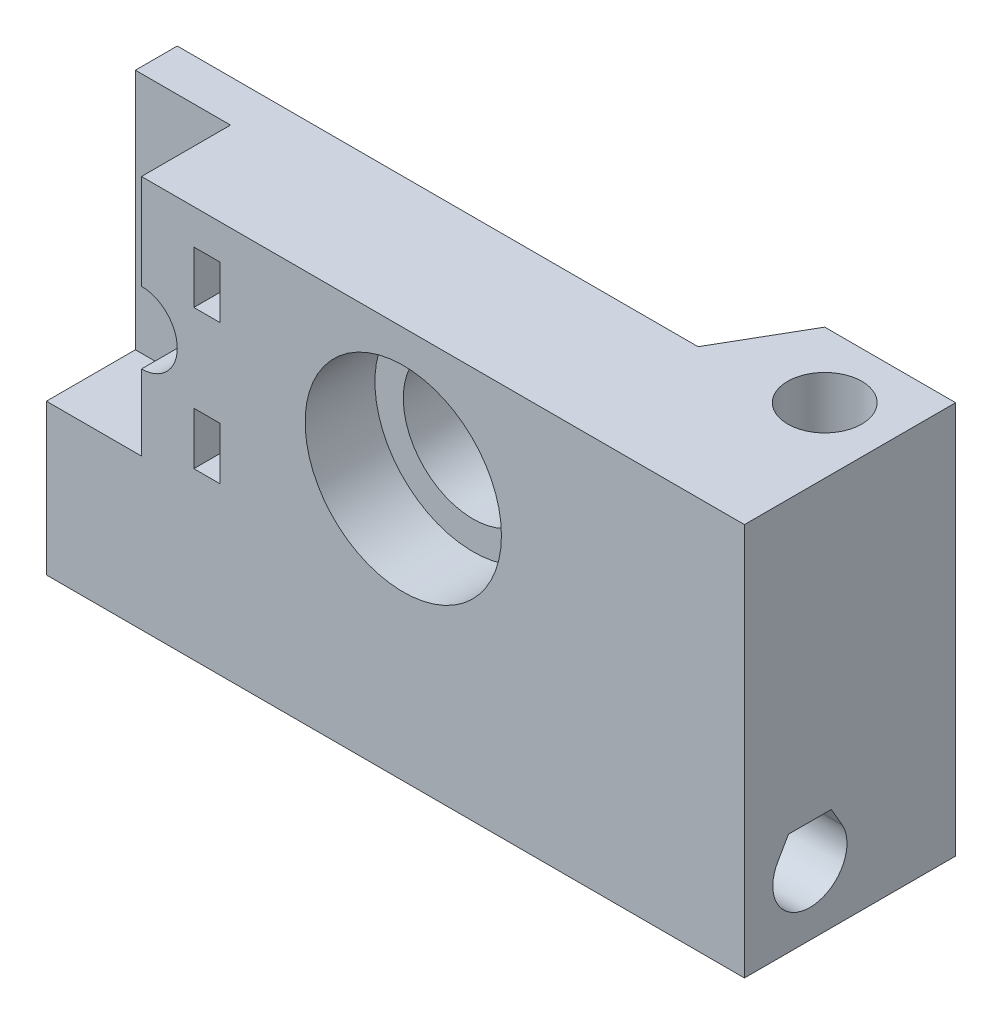
SolidWorks part; units mm, degrees
ref_plane "Piano frontale" through (0, 0, 0) normal (0, 0, 1) x (1, 0, 0)
ref_plane "Piano superiore" through (0, 0, 0) normal (0, 1, 0) x (1, 0, 0)
ref_plane "Piano destro" through (0, 0, 0) normal (1, 0, 0) x (0, 0, -1)
sketch "Schizzo2" plane through (0, 0, 0) normal (0, 0, 1) x (1, 0, 0)
  line L1 (40, -15) -> (-40, -15)
  line L2 (40, -15) -> (40, 15)
  line L3 (40, 15) -> (-40, 15)
  line L4 (-40, -15) -> (-40, 15)
  line L5 (40, -15) -> (-40, 15) construction
  line L6 (40, 15) -> (-40, -15) construction
  point P0 (0, 0)
  dimension "D1" = 30
  dimension "D2" = 80
extrude "Estrusione-Estrusione1" add sketch "Schizzo2" along normal mid plane 24.2
sketch "Schizzo3" plane through (0, -15, 0) normal (0, -1, 0) x (1, 0, 0)
  line L1 (40, 12.1) -> (40, -12.1) construction
  line L2 (-40, -12.1) -> (40, -12.1) construction
  circle A0 centre (32.5, -4.6) radius 4.25
  dimension "D2" = 8.5
  dimension "D1" = 7.5
  dimension "D3" = 7.5
extrude "Taglio-Estrusione1" cut sketch "Schizzo3" against normal through all contours A0
sketch "Schizzo4" plane through (0, 0, 12.1) normal (0, 0, 1) x (1, 0, 0)
  line L0 (0, 0) -> (0.9, 0) construction
  line L1 (28.25, -15) -> (36.75, -15) construction
  line L2 (28.25, -15) -> (36.75, -15) construction
  line L3 (32.5, -15) -> (32.5, 15) construction
  line L4 (40, 15) -> (-40, 15) construction
  circle A0 centre (0.9, 0) radius 11.25
  dimension "D1" = 22.5
  dimension "D2" = 31.6
extrude "Taglio-Estrusione2" cut sketch "Schizzo4" against normal blind 8
sketch "Schizzo5" plane through (0, 0, 4.1) normal (0, 0, 1) x (1, 0, 0)
  circle A0 centre (0.9, 0) radius 11.25 construction
  circle A1 centre (0.9, 0) radius 11.25 construction
  circle A2 centre (0.9, 0) radius 8
  dimension "D1" = 16
extrude "Taglio-Estrusione3" cut sketch "Schizzo5" against normal through all contours A2
sketch "Schizzo6" plane through (0, -15, 0) normal (0, 1, 0) x (1, 0, 0)
  line L4 (40, 12.1) -> (-40, 12.1)
  line L5 (-40, 12.1) -> (-40, -12.1)
  line L6 (-40, -12.1) -> (40, -12.1)
  line L7 (40, -12.1) -> (40, 12.1)
  line L8 (40, 12.1) -> (-40, 12.1)
  line L9 (-40, 12.1) -> (-40, -12.1)
  line L10 (-40, -12.1) -> (40, -12.1)
  line L11 (40, -12.1) -> (40, 12.1)
  circle A0 centre (32.5, 4.6) radius 4.25 construction
  circle A1 centre (32.5, 4.6) radius 4.25
  dimension "D1" = 0
extrude "Estrusione-Estrusione2" add sketch "Schizzo6" against normal blind 15
sketch "Schizzo7" plane through (40, 0, 0) normal (1, 0, 0) x (0, 0, -1)
  line L0 (-2.1463, -18.25) -> (-7.0537, -18.25)
  line L1 (-7.0537, -18.25) -> (-8.2806, -20.375)
  line L2 (-12.1, -30) -> (12.1, -30) construction
  line L3 (-2.1463, -18.25) -> (-0.9194, -20.375)
  line L4 (-12.1, 15) -> (-12.1, -30) construction
  arc A0 (-8.2806, -20.375) -> (-0.9194, -20.375) centre (-4.6, -22.5) ccw
  point P9 (-4.6, -18.25)
  dimension "D2" = 8.5
  dimension "D1" = 7.5
  dimension "D3" = 7.5
  dimension "D4" = 120
extrude "Taglio-Estrusione4" cut sketch "Schizzo7" against normal through all
sketch "Schizzo8" plane through (0, 0, 12.1) normal (0, 0, 1) x (1, 0, 0)
  line L0 (-29.1, 0) -> (0.9, 0) construction
  circle A0 centre (0.9, 0) radius 11.25 construction
  circle A1 centre (0.9, 0) radius 11.25 construction
  circle A2 centre (-29.1, 0) radius 4.1
  dimension "D2" = 8.2
  dimension "D1" = 30
sketch "Schizzo9" plane through (0, 15, 0) normal (0, -1, 0) x (1, 0, 0)
  line L0 (25, -12.1) -> (19.6884, -2.9)
  line L2 (19.6884, -2.9) -> (-40, -2.9)
  line L4 (-40, -2.9) -> (-40, -12.1)
  line L5 (-40, -12.1) -> (25, -12.1)
  line L7 (40, -12.1) -> (-40, -12.1) construction
  line L8 (40, 12.1) -> (-40, 12.1) construction
  dimension "D1" = 15
  dimension "D2" = 60
  dimension "D3" = 15
extrude "Taglio-Estrusione5" cut sketch "Schizzo9" along normal through all
extrude "Taglio-Estrusione6" cut sketch "Schizzo8" against normal blind 12 contours A2
sketch "Schizzo10" plane through (-40, 0, 0) normal (-1, 0, 0) x (0, 0, 1)
  line L0 (1.9, 15) -> (1.9, -12.75)
  line L2 (1.9, 15) -> (12.1, 15)
  line L3 (12.1, -30) -> (12.1, 15) construction
  line L5 (12.1, -4.1) -> (12.1, 4.1) construction
  line L6 (12.1, -4.1) -> (12.1, 4.1) construction
  line L7 (12.1, 0) -> (1.9, 0) construction
  line L9 (1.9, -12.75) -> (12.1, -12.75)
  line L10 (12.1, -12.75) -> (12.1, 15)
  point P15 (7.1, 0)
  dimension "D2" = 12.75
  dimension "D1" = 10.2
extrude "Taglio-Estrusione7" cut sketch "Schizzo10" against normal blind 10.9 contours L0 L9 L10 L2
sketch "Schizzo11" plane through (-29.1, 0, 0) normal (-1, 0, 0) x (0, 0, 1)
  line L0 (12.1, -4.1) -> (12.1, 4.1) construction
  line L1 (12.1, -4.1) -> (12.1, 4.1) construction
  line L2 (12.1, 0) -> (7.1, 0) construction
  line L3 (7.1, -8) -> (7.1, 8) construction
  line L4 (8.1104, 6.25) -> (6.0896, 6.25)
  line L5 (8.1104, -9.75) -> (6.0896, -9.75)
  line L6 (8.1104, -9.75) -> (8.6155, -8.875)
  line L7 (6.0896, -9.75) -> (5.5845, -8.875)
  line L8 (8.1104, 6.25) -> (8.6155, 7.125)
  line L9 (6.0896, 6.25) -> (5.5845, 7.125)
  arc A0 (8.6155, 7.125) -> (5.5845, 7.125) centre (7.1, 8) ccw
  arc A1 (8.6155, -8.875) -> (5.5845, -8.875) centre (7.1, -8) ccw
  point P8 (7.1, 0)
  point P13 (7.1, 6.25)
  point P16 (7.1, -9.75)
  dimension "D3" = 3.5
  dimension "D1" = 5
  dimension "D2" = 8
  dimension "D4" = 120
  dimension "D5" = 120
extrude "Taglio-Estrusione8" cut sketch "Schizzo11" against normal blind 12
sketch "Schizzo12" plane through (0, 0, 12.1) normal (0, 0, 1) x (1, 0, 0)
  line L0 (-21.6, -8) -> (-21.6, 8) construction
  line L1 (-23.1, -11) -> (-20.1, -11)
  line L2 (-23.1, -11) -> (-23.1, -5)
  line L3 (-23.1, -5) -> (-20.1, -5)
  line L4 (-20.1, -11) -> (-20.1, -5)
  line L5 (-23.1, -11) -> (-20.1, -5) construction
  line L6 (-23.1, -5) -> (-20.1, -11) construction
  line L7 (-23.1, 5) -> (-20.1, 5)
  line L8 (-23.1, 5) -> (-23.1, 11)
  line L9 (-23.1, 11) -> (-20.1, 11)
  line L10 (-20.1, 5) -> (-20.1, 11)
  line L11 (-23.1, 5) -> (-20.1, 11) construction
  line L12 (-23.1, 11) -> (-20.1, 5) construction
  line L13 (-29.1, 0) -> (-21.6, 0) construction
  arc A1 (-29.1, -4.1) -> (-29.1, 4.1) centre (-29.1, 0) ccw construction
  arc A2 (-29.1, -4.1) -> (-29.1, 4.1) centre (-29.1, 0) ccw construction
  point P3 (-21.6, -8)
  point P8 (-21.6, 8)
  dimension "D1" = 8
  dimension "D2" = 6
  dimension "D3" = 3
  dimension "D4" = 7.5
extrude "Taglio-Estrusione9" cut sketch "Schizzo12" against normal blind 8.2
